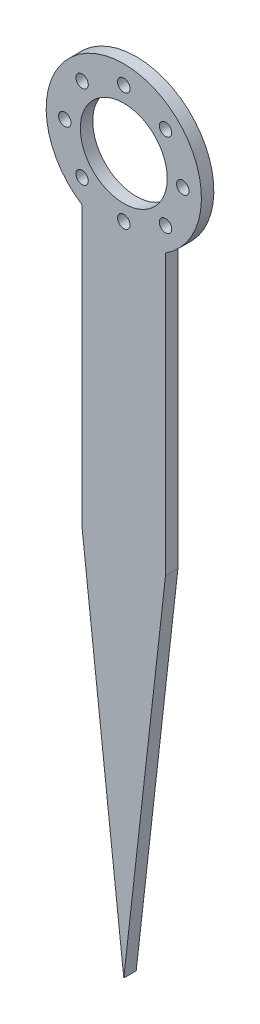
SolidWorks part; units mm, degrees
ref_plane "前视基准面" through (0, 0, 0) normal (0, 0, 1) x (1, 0, 0)
ref_plane "上视基准面" through (0, 0, 0) normal (0, 1, 0) x (1, 0, 0)
ref_plane "右视基准面" through (0, 0, 0) normal (1, 0, 0) x (0, 0, -1)
sketch "草图1" plane through (0, 0, 0) normal (0, 0, 1) x (1, 0, 0)
  line L0 (-13.435, -21.0832) -> (-13.435, -111.0832)
  line L1 (-13.435, -111.0832) -> (0, -230)
  line L2 (0, -230) -> (13.435, -111.0832)
  line L3 (13.435, -111.0832) -> (13.435, -21.0832)
  circle A11 centre (0, 0) radius 19 construction
  circle A12 centre (0, 0) radius 14
  circle A13 centre (0, 19) radius 2
  circle A14 centre (13.435, 13.435) radius 2
  circle A15 centre (19, 0) radius 2
  circle A16 centre (13.435, -13.435) radius 2
  circle A17 centre (0, -19) radius 2
  circle A18 centre (-13.435, -13.435) radius 2
  circle A19 centre (-19, 0) radius 2
  circle A20 centre (-13.435, 13.435) radius 2
  circle A21 centre (0, 0) radius 25 construction
  arc A22 (-13.435, -21.0832) -> (13.435, -21.0832) centre (0, 0) cw
  dimension "D1" = 38
  dimension "D2" = 28
  dimension "D3" = 4
  dimension "D4" = 90
  dimension "D5" = 50
  dimension "D6" = 230
extrude "凸台-拉伸1" add sketch "草图1" along normal blind 4
